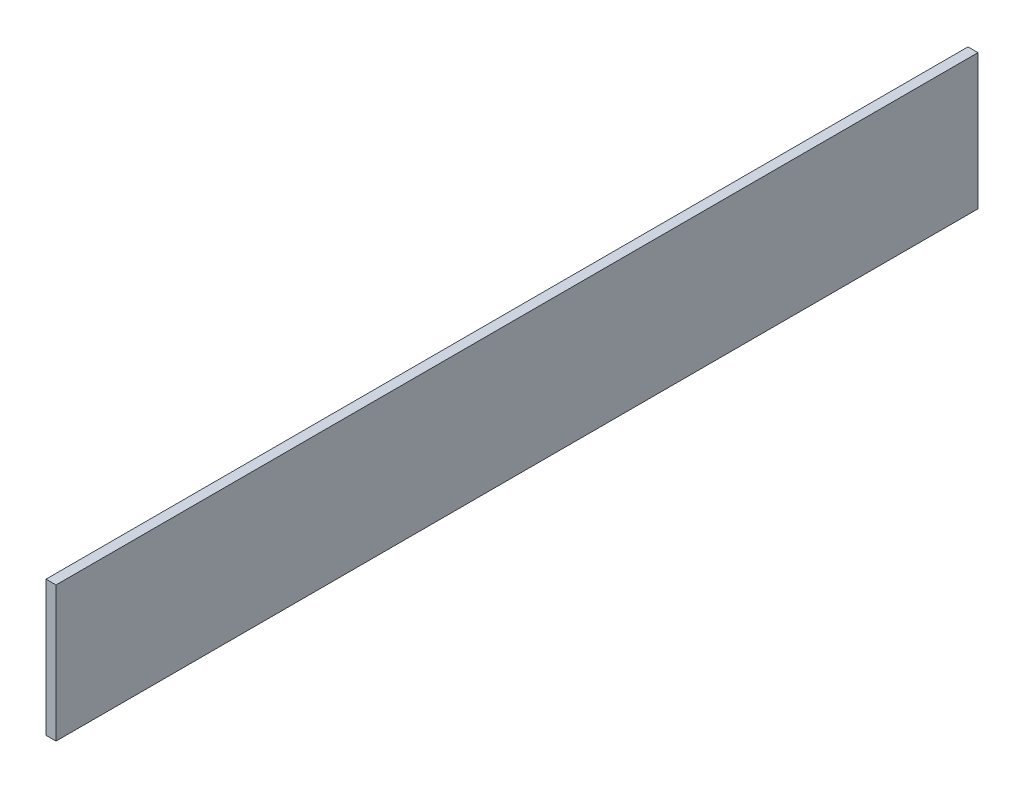
SolidWorks part; units mm, degrees
ref_plane "Alzado" through (0, 0, 0) normal (0, 0, 1) x (1, 0, 0)
ref_plane "Planta" through (0, 0, 0) normal (0, 1, 0) x (1, 0, 0)
ref_plane "Vista lateral" through (0, 0, 0) normal (1, 0, 0) x (0, 0, -1)
sketch "Croquis1" plane through (0, 0, 0) normal (0, 0, 1) x (1, 0, 0)
  line L1 (5, -67.5) -> (-5, -67.5)
  line L2 (5, -67.5) -> (5, 67.5)
  line L3 (5, 67.5) -> (-5, 67.5)
  line L4 (-5, -67.5) -> (-5, 67.5)
  line L5 (5, -67.5) -> (-5, 67.5) construction
  line L6 (5, 67.5) -> (-5, -67.5) construction
  point P0 (0, 0)
  dimension "D1" = 135
  dimension "D2" = 10
extrude "Saliente-Extruir1" add sketch "Croquis1" along normal blind 920
